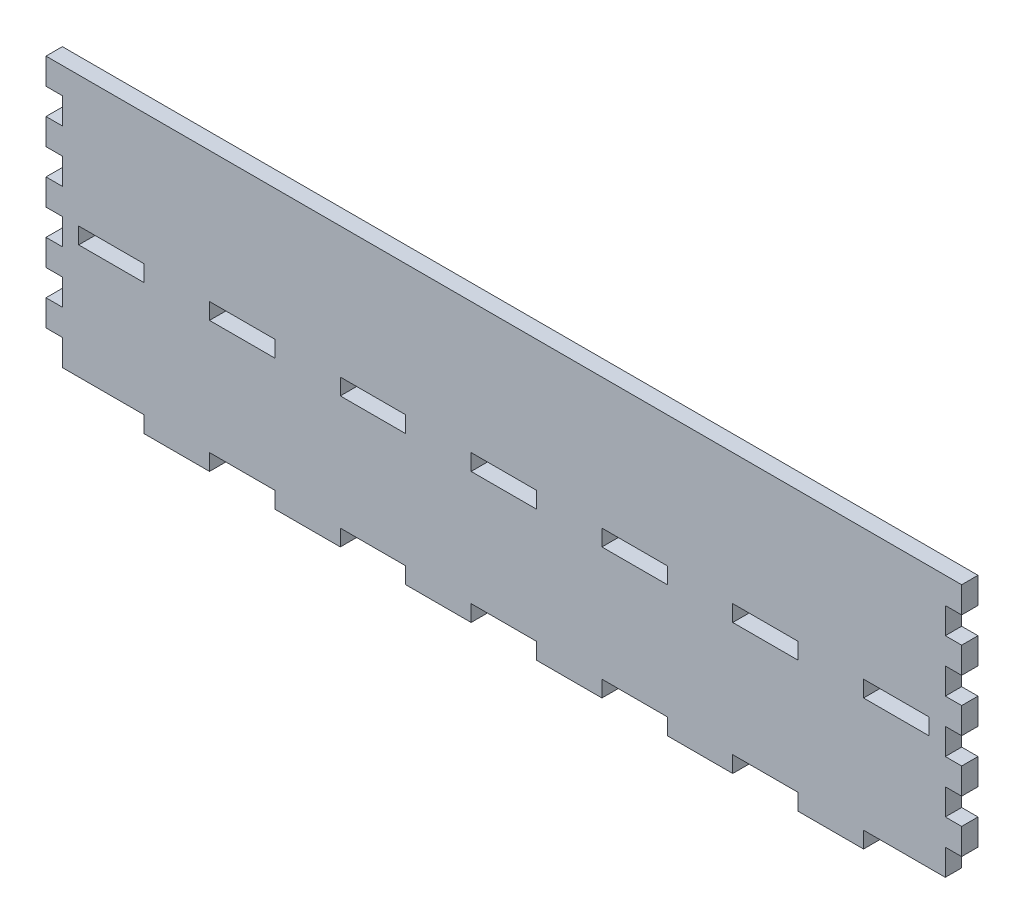
SolidWorks part; units mm, degrees
material "Pin"
ref_plane "Front" through (0, 0, 0) normal (0, 0, 1) x (1, 0, 0)
ref_plane "Top" through (0, 0, 0) normal (0, 1, 0) x (1, 0, 0)
ref_plane "Right" through (0, 0, 0) normal (1, 0, 0) x (0, 0, -1)
sketch "Esquisse1" plane through (0, 0, 0) normal (0, 0, 1) x (1, 0, 0)
  line L1 (-177.8, 53.975) -> (177.8, 53.975)
  line L2 (-177.8, 53.975) -> (-177.8, -53.975)
  line L3 (-177.8, -53.975) -> (177.8, -53.975)
  line L4 (177.8, 53.975) -> (177.8, -53.975)
  line L5 (-177.8, 53.975) -> (177.8, -53.975) construction
  line L6 (-177.8, -53.975) -> (177.8, 53.975) construction
  point P0 (0, 0)
  dimension "D1" = 355.6
  dimension "D2" = 107.95
extrude "Boss.-Extru.1" add sketch "Esquisse1" along normal blind 6.35
sketch "Esquisse4" plane through (0, 0, 6.35) normal (0, 0, 1) x (1, 0, 0)
  line L0 (-177.8, 53.975) -> (-177.8, -53.975) construction
  line L1 (-177.8, 43.815) -> (-171.45, 43.815)
  line L2 (-177.8, 43.815) -> (-177.8, 33.655)
  line L3 (-177.8, 33.655) -> (-171.45, 33.655)
  line L4 (-171.45, 43.815) -> (-171.45, 33.655)
  line L5 (177.8, 53.975) -> (-177.8, 53.975) construction
  dimension "D1" = 6.35
  dimension "D2" = 10.16
  dimension "D3" = 10.16
extrude "Enlèv. mat.-Extru.3" cut sketch "Esquisse4" against normal blind 6.35
pattern_linear "Répétition linéaire2" count 7 spacing 20.32 along (0, -1, 0) count 2 spacing 349.25 along (1, 0, 0) of "Enlèv. mat.-Extru.3"
sketch "Esquisse5" plane through (0, 0, 6.35) normal (0, 0, 1) x (1, 0, 0)
  line L0 (-177.8, -53.975) -> (177.8, -53.975) construction
  line L1 (-165.1, -53.975) -> (-139.7, -53.975)
  line L2 (-165.1, -53.975) -> (-165.1, -47.625)
  line L3 (-165.1, -47.625) -> (-139.7, -47.625)
  line L4 (-139.7, -53.975) -> (-139.7, -47.625)
  line L5 (-177.8, -47.625) -> (-177.8, -53.975) construction
  dimension "D1" = 6.35
  dimension "D2" = 25.4
  dimension "D3" = 12.7
extrude "Enlèv. mat.-Extru.4" cut sketch "Esquisse5" against normal blind 6.35
pattern_linear "Répétition linéaire3" count 7 spacing 50.8 along (1, 0, 0) of "Enlèv. mat.-Extru.4"
sketch "Esquisse6" plane through (0, 0, 6.35) normal (0, 0, 1) x (1, 0, 0)
  line L1 (-177.8, -53.975) -> (-165.1, -53.975)
  line L2 (-177.8, -53.975) -> (-177.8, -47.625)
  line L3 (-177.8, -47.625) -> (-165.1, -47.625)
  line L4 (-165.1, -53.975) -> (-165.1, -47.625)
  dimension "D1" = 6.35
  dimension "D2" = 12.7
extrude "Enlèv. mat.-Extru.5" cut sketch "Esquisse6" against normal blind 6.35
sketch "Esquisse8" plane through (0, 0, 6.35) normal (0, 0, 1) x (1, 0, 0)
  line L1 (177.8, -53.975) -> (165.1, -53.975)
  line L2 (177.8, -53.975) -> (177.8, -47.625)
  line L3 (177.8, -47.625) -> (165.1, -47.625)
  line L4 (165.1, -53.975) -> (165.1, -47.625)
extrude "Enlèv. mat.-Extru.7" cut sketch "Esquisse8" against normal blind 6.35
sketch "Esquisse9" plane through (0, 0, 6.35) normal (0, 0, 1) x (1, 0, 0)
  line L0 (-139.7, -47.625) -> (-171.45, -47.625) construction
  line L1 (-165.1, -3.175) -> (-139.7, -3.175)
  line L2 (-165.1, -3.175) -> (-165.1, 3.175)
  line L3 (-165.1, 3.175) -> (-139.7, 3.175)
  line L4 (-139.7, -3.175) -> (-139.7, 3.175)
  line L5 (-171.45, -6.985) -> (-171.45, 3.175) construction
  dimension "D1" = 6.35
  dimension "D2" = 25.4
  dimension "D3" = 44.45
  dimension "D4" = 6.35
extrude "Enlèv. mat.-Extru.8" cut sketch "Esquisse9" against normal blind 6.35
pattern_linear "Répétition linéaire6" count 7 spacing 50.8 along (1, 0, 0) of "Enlèv. mat.-Extru.8"
sketch "Esquisse11" plane through (0, 0, 6.35) normal (0, 0, 1) x (1, 0, 0)
  line L0 (12.7, 3.175) -> (-12.7, 3.175) construction
  text T0 "<b>4</b>" font "Britannic Bold" height 19.05
  text T1 "<b>5</b>" font "Britannic Bold" height 19.05
  text T2 "<b>6</b>" font "Britannic Bold" height 19.05
  dimension "D1" = 6.35
  dimension "D2" = 19.05
  dimension "D3" = 114.3
  dimension "D4" = 114.3
